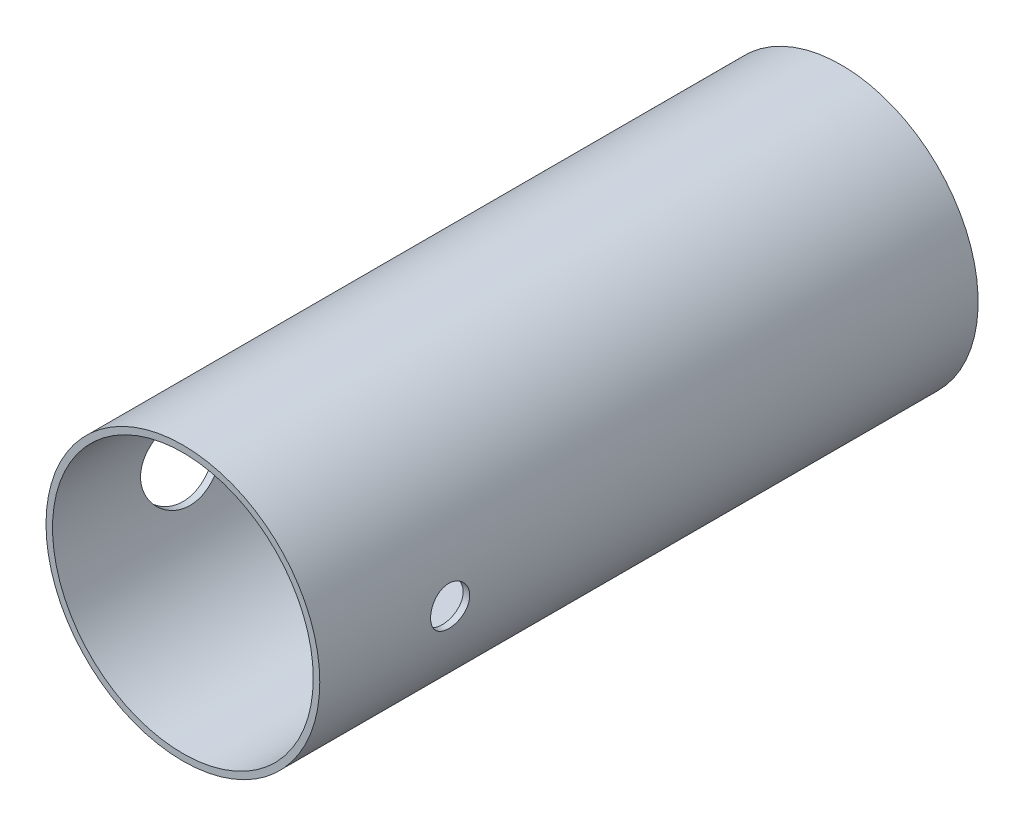
SolidWorks part; units mm, degrees
material "6061 Alloy"
ref_plane "Front Plane" through (0, 0, 0) normal (0, 0, 1) x (1, 0, 0)
ref_plane "Top Plane" through (0, 0, 0) normal (0, 1, 0) x (1, 0, 0)
ref_plane "Right Plane" through (0, 0, 0) normal (1, 0, 0) x (0, 0, -1)
sketch "Sketch1" plane through (0, 0, 0) normal (0, 0, 1) x (1, 0, 0)
  circle A0 centre (0, 0) radius 20
  circle A1 centre (0, 0) radius 21
  dimension "D1" = 40
  dimension "D2" = 42
extrude "Boss-Extrude1" add sketch "Sketch1" along normal blind 100
ref_plane "Plane1" through (-21, 0, 0) normal (-1, 0, 0) x (0, 0, 1)
sketch "Sketch2" plane through (-21, 0, 0) normal (-1, 0, 0) x (0, 0, 1)
  line L0 (100, -21) -> (100, 21) construction
  line L1 (100, 21) -> (0, 21) construction
  circle A0 centre (80, 0) radius 6.5
  dimension "D1" = 13
  dimension "D2" = 20
  dimension "D3" = 21
extrude "Cut-Extrude1" cut sketch "Sketch2" against normal up to next
sketch "Sketch5" plane through (-21, 0, 0) normal (-1, 0, 0) x (0, 0, 1)
  circle A0 centre (80, 0) radius 3
  dimension "D1" = 6
extrude "Cut-Extrude3" cut sketch "Sketch5" against normal up to next
sketch "Sketch3" plane through (0, 0, 0) normal (0, 0, -1) x (-1, 0, 0)
  circle A0 centre (0, 0) radius 21
extrude "Boss-Extrude2" add sketch "Sketch3" along normal blind 1
sketch "Sketch4" plane through (0, 0, -1) normal (0, 0, -1) x (-1, 0, 0)
  circle A2 centre (2.6323, 6.4862) radius 6.5
  dimension "D1" = 13
extrude "Cut-Extrude2" cut sketch "Sketch4" against normal up to next
